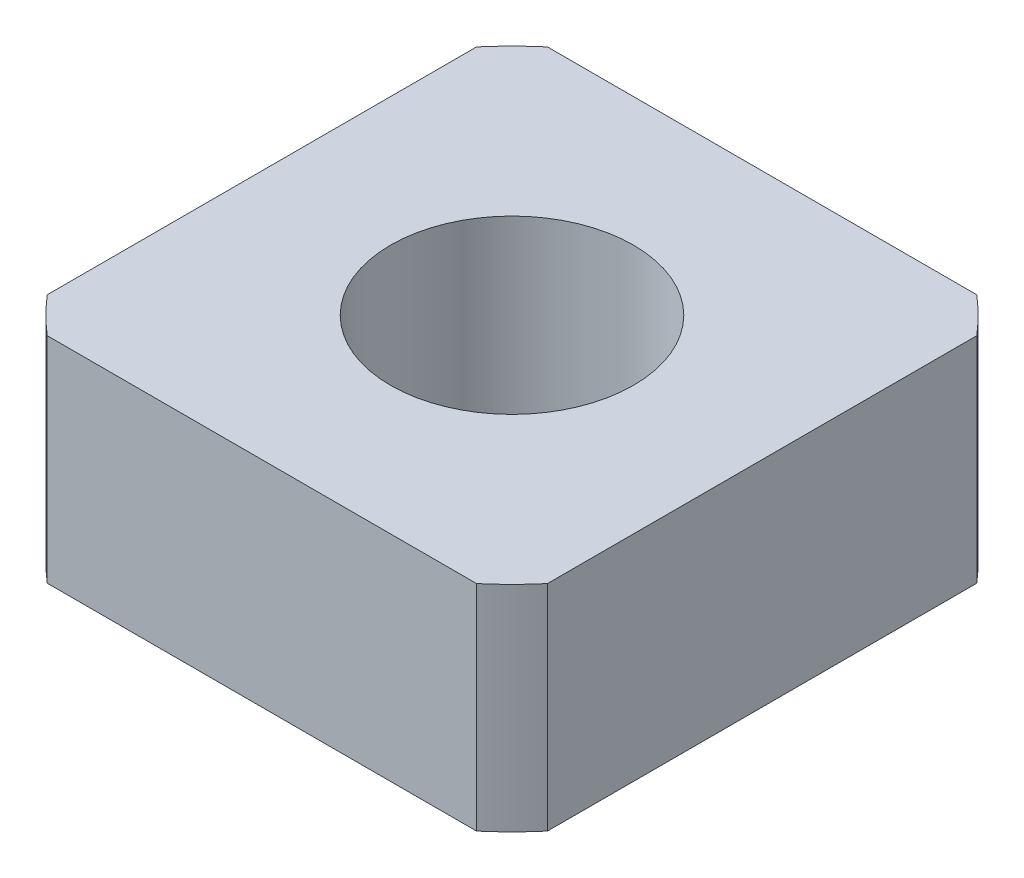
SolidWorks part; units mm, degrees
ref_plane "Front" through (0, 0, 0) normal (0, 0, 1) x (1, 0, 0)
ref_plane "Top" through (0, 0, 0) normal (0, 1, 0) x (1, 0, 0)
ref_plane "Right" through (0, 0, 0) normal (1, 0, 0) x (0, 0, -1)
sketch "Sketch1" plane through (0, 0, 0) normal (0, 1, 0) x (1, 0, 0)
  line L0 (0, 0) -> (-3.5, 0)
  line L1 (-3.5, 0) -> (-3.5, 3.5)
  line L2 (0, 0) -> (3.5, 0)
  line L3 (3.5, 0) -> (3.5, 3.5)
  line L4 (3.5, 3.5) -> (-3.5, 3.5)
  line L5 (-3.5, 0) -> (-3.5, -3.5)
  line L6 (-3.5, -3.5) -> (3.5, -3.5)
  line L7 (3.5, -3.5) -> (3.5, 0)
  circle A0 centre (0, 0) radius 4.6127
  circle A1 centre (0, 0) radius 1.7
  dimension "D1" = 3.5
  dimension "D2" = 3.5
  dimension "D3" = 3.5
  dimension "D4" = 3.5
extrude "Boss-Extrude1" add sketch "Sketch1" along normal blind 3 contours A1 L0 L5 A0 L6 L7 L2 | A1 L2 L3 A0 L4 L1 L0
